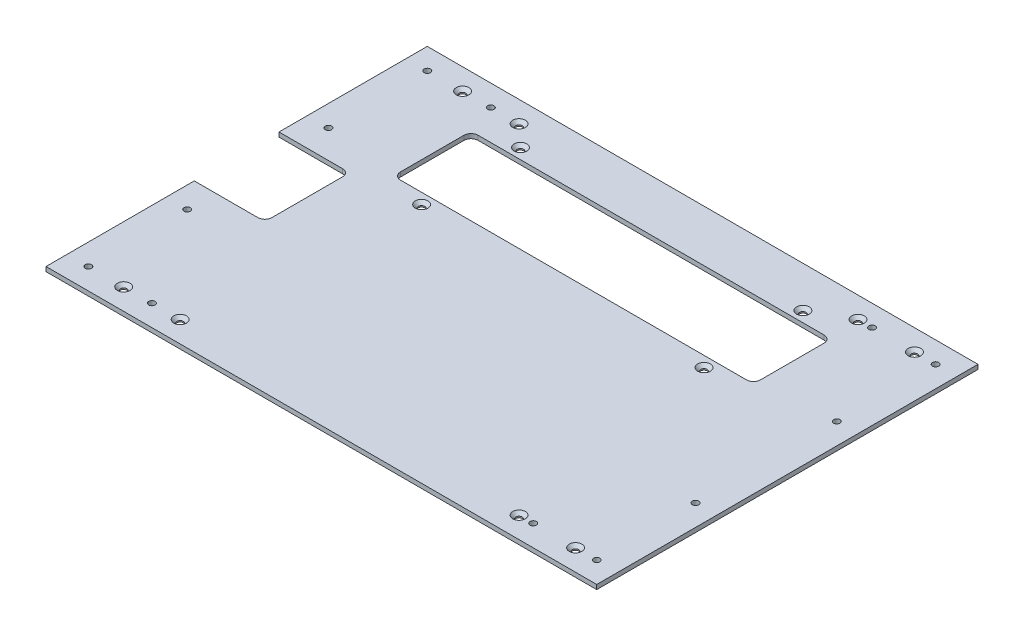
SolidWorks part; units mm, degrees
ref_plane "Front Plane" through (0, 0, 0) normal (0, 0, 1) x (1, 0, 0)
ref_plane "Top Plane" through (0, 0, 0) normal (0, 1, 0) x (1, 0, 0)
ref_plane "Right Plane" through (0, 0, 0) normal (1, 0, 0) x (0, 0, -1)
sketch "Sketch1" plane through (0, 0, 0) normal (0, 1, 0) x (1, 0, 0)
  line L1 (-195, -135) -> (195, -135)
  line L2 (-195, -135) -> (-195, 135)
  line L3 (-195, 135) -> (195, 135)
  line L4 (195, -135) -> (195, 135)
  line L5 (-195, -135) -> (195, 135) construction
  line L6 (-195, 135) -> (195, -135) construction
  point P0 (0, 0)
  dimension "D1" = 390
  dimension "D2" = 270
extrude "Boss-Extrude1" add sketch "Sketch1" along normal blind 3.175
hole_wizard "CSK for M4 SFHCS2" positions "Sketch4" profile "Sketch6" countersink size "M4" standard "ANSI Metric" end condition through all
sketch "Sketch4" plane through (0, 3.175, 0) normal (0, 1, 0) x (1, 0, 0)
  line L0 (-155, 120) -> (-115, 120)
  line L2 (125, 120) -> (165, 120)
  line L4 (195, 135) -> (-195, 135) construction
  point P1 (-155, 120)
  point P2 (-115, 120)
  point P5 (125, 120)
  point P6 (165, 120)
  point P11 (-135, 120)
  point P13 (145, 120)
  dimension "D1" = 40
  dimension "D2" = 40
  dimension "D3" = 15
  dimension "D4" = 60
  dimension "D5" = 50
sketch "Sketch6" plane through (-155, 3.175, -120) normal (1, 0, 0) x (0, 0, 1)
  line L0 (0, 0) -> (0, 3.175)
  line L1 (0, 3.175) -> (2.25, 3.175)
  line L2 (2.25, 3.175) -> (2.25, 2.23)
  line L3 (2.25, 2.23) -> (4.48, 0)
  line L5 (4.48, 0) -> (0, 0)
  line L6 (-2.25, 2.23) -> (-4.48, 0) construction
  line L11 (0, -6.35) -> (0, 107.95) construction
  dimension "Thru Hole Dia." = 4.5
  dimension "Thru Hole Depth" = 3.175
  dimension "Near C'Sink Dia." = 8.96
  dimension "Near C'Sink Angle" = 90
mirror "Mirror2" about plane through (0, 0, 0) normal (0, 0, 1) of "CSK for M4 SFHCS2"
hole_wizard "M4 Clearance Hole1" positions "Sketch7" profile "Sketch9" hole size "M4" standard "ANSI Metric" end condition through all
sketch "Sketch7" plane through (0, 3.175, 0) normal (0, 1, 0) x (1, 0, 0)
  line L0 (-195, 135) -> (-195, -135) construction
  line L1 (195, 135) -> (-195, 135) construction
  point P0 (-180, 120)
  point P2 (-180, 50)
  point P4 (-135, 120)
  dimension "D1" = 15
  dimension "D2" = 15
  dimension "D3" = 45
  dimension "D4" = 70
sketch "Sketch9" plane through (-180, 3.175, -120) normal (1, 0, 0) x (0, 0, 1)
  line L0 (0, 0) -> (0, 3.175)
  line L1 (0, 3.175) -> (2.25, 3.175)
  line L2 (2.25, 3.175) -> (2.25, 0)
  line L5 (2.25, 0) -> (0, 0)
  line L11 (0, -6.35) -> (0, 107.95) construction
  dimension "Thru Hole Dia." = 4.5
  dimension "Thru Hole Depth" = 3.175
mirror "Mirror3" about plane through (0, 0, 0) normal (1, 0, 0) of "M4 Clearance Hole1" second plane through (0, 0, 0) second plane normal (0, 0, 1)
sketch "Sketch10" plane through (0, 3.175, 0) normal (0, 1, 0) x (1, 0, 0)
  line L0 (195, 135) -> (-195, 135) construction
  line L1 (-127.5, 43.5) -> (127.5, 43.5)
  line L2 (-127.5, 43.5) -> (-127.5, 98.5)
  line L3 (-127.5, 98.5) -> (127.5, 98.5)
  line L4 (127.5, 43.5) -> (127.5, 98.5)
  line L5 (-127.5, 43.5) -> (127.5, 98.5) construction
  line L6 (-127.5, 98.5) -> (127.5, 43.5) construction
  point P0 (0, 71)
  dimension "D1" = 255
  dimension "D2" = 55
  dimension "D3" = 64
extrude "Cut-Extrude1" cut sketch "Sketch10" against normal blind 3.175
sketch "Sketch11" plane through (0, 3.175, 0) normal (0, 1, 0) x (1, 0, 0)
  line L0 (-195, 135) -> (-195, -135) construction
  line L1 (-145, -30) -> (-195, -30)
  line L2 (-145, -30) -> (-145, 30)
  line L3 (-145, 30) -> (-195, 30)
  line L4 (-195, -30) -> (-195, 30)
  line L5 (-145, -30) -> (-195, 30) construction
  line L6 (-145, 30) -> (-195, -30) construction
  point P0 (-170, 0)
  point P7 (-195, 0)
  dimension "D1" = 60
  dimension "D2" = 50
  dimension "D3" = 0
extrude "Cut-Extrude2" cut sketch "Sketch11" against normal blind 10
hole_wizard "CSK for M4 SFHCS3" positions "Sketch12" profile "Sketch13" countersink size "M4" standard "ANSI Metric" end condition through all
sketch "Sketch12" plane through (0, 3.175, 0) normal (0, 1, 0) x (1, 0, 0)
  line L1 (-100, 36) -> (100, 36)
  line L2 (-100, 36) -> (-100, 106)
  line L3 (-100, 106) -> (100, 106)
  line L4 (100, 36) -> (100, 106)
  line L5 (-100, 36) -> (100, 106) construction
  line L6 (-100, 106) -> (100, 36) construction
  line L7 (127.5, 98.5) -> (-127.5, 98.5) construction
  point P2 (100, 106)
  point P131 (-100, 36)
  point P132 (-100, 106)
  point P133 (100, 36)
  point P141 (0, 71)
  dimension "D1" = 200
  dimension "D2" = 70
  dimension "D3" = 7.5
sketch "Sketch13" plane through (100, 3.175, -106) normal (1, 0, 0) x (0, 0, 1)
  line L0 (0, 0) -> (0, 3.175)
  line L1 (0, 3.175) -> (2.25, 3.175)
  line L2 (2.25, 3.175) -> (2.25, 2.23)
  line L3 (2.25, 2.23) -> (4.48, 0)
  line L5 (4.48, 0) -> (0, 0)
  line L6 (-2.25, 2.23) -> (-4.48, 0) construction
  line L11 (0, -6.35) -> (0, 107.95) construction
  dimension "Thru Hole Dia." = 4.5
  dimension "Thru Hole Depth" = 3.175
  dimension "Near C'Sink Dia." = 8.96
  dimension "Near C'Sink Angle" = 90
fillet "Fillet1" radius 5 4 edges at (127.5, 1.5875, -43.5) (127.5, 1.5875, -98.5) (-127.5, 1.5875, -43.5) (-127.5, 1.5875, -98.5)
fillet "Fillet2" radius 5 2 edges at (-145, 1.5875, 30) (-145, 1.5875, -30)
